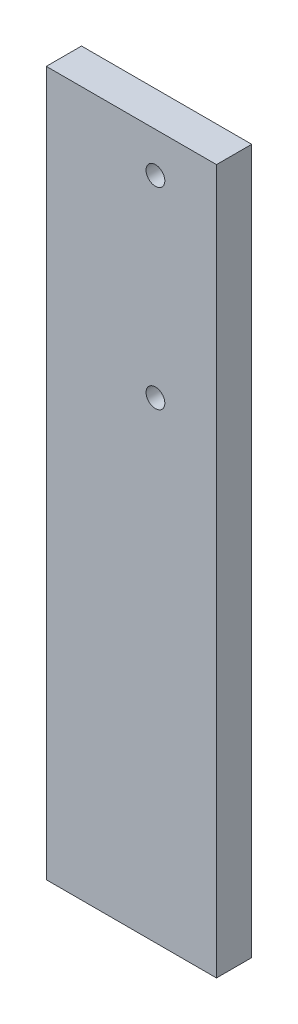
SolidWorks part; units mm, degrees
ref_plane "Alzado" through (0, 0, 0) normal (0, 0, 1) x (1, 0, 0)
ref_plane "Planta" through (0, 0, 0) normal (0, 1, 0) x (1, 0, 0)
ref_plane "Vista lateral" through (0, 0, 0) normal (1, 0, 0) x (0, 0, -1)
sketch "Croquis1" plane through (0, 0, 0) normal (0, 0, 1) x (1, 0, 0)
  line L1 (0, 0) -> (72.48, 0)
  line L2 (0, 0) -> (0, 300)
  line L3 (0, 300) -> (72.48, 300)
  line L4 (72.48, 0) -> (72.48, 300)
  circle A0 centre (46.48, 283) radius 4
  circle A1 centre (46.48, 201) radius 4
  dimension "D3" = 8
  dimension "D1" = 300
  dimension "D2" = 72.48
  dimension "D4" = 82
  dimension "D5" = 17
  dimension "D6" = 26
extrude "Saliente-Extruir1" add sketch "Croquis1" along normal blind 15
